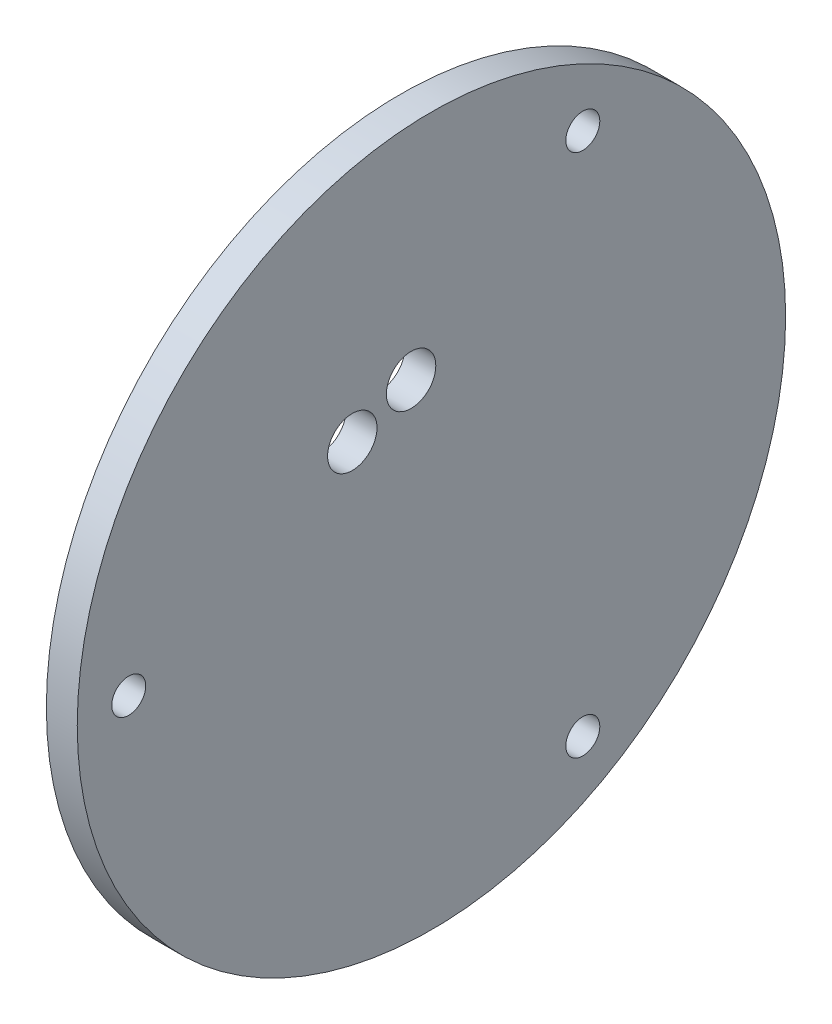
SolidWorks part; units mm, degrees
ref_plane "Front Plane" through (0, 0, 0) normal (0, 0, 1) x (1, 0, 0)
ref_plane "Top Plane" through (0, 0, 0) normal (0, 1, 0) x (1, 0, 0)
ref_plane "Right Plane" through (0, 0, 0) normal (1, 0, 0) x (0, 0, -1)
sketch "Axial profile (mm)" plane through (0, 0, 0) normal (0, 0, 1) x (1, 0, 0)
  line L0 (-110, 0) -> (75, 0) construction
  line L1 (156.7, 0) -> (159.7, 0)
  line L2 (159.7, 0) -> (159.7, 34.4)
  line L3 (159.7, 34.4) -> (156.7, 34.4)
  line L4 (156.7, 34.4) -> (156.7, 0)
revolve "Full revolution" add sketch "Axial profile (mm)" angle 360 about L0
sketch "Sketch2" plane through (0, 0, 0) normal (1, 0, 0) x (0, 0, -1)
  circle A0 centre (-1.9774, 12.8487) radius 2.4
  circle A1 centre (-7.6872, 10.4836) radius 2.4
  circle A2 centre (-29.4, 0) radius 1.65
  circle A3 centre (14.7, -25.4611) radius 1.65
  circle A4 centre (14.7, 25.4611) radius 1.65
extrude "Axial holes" cut sketch "Sketch2" against normal through all and the other way through all
